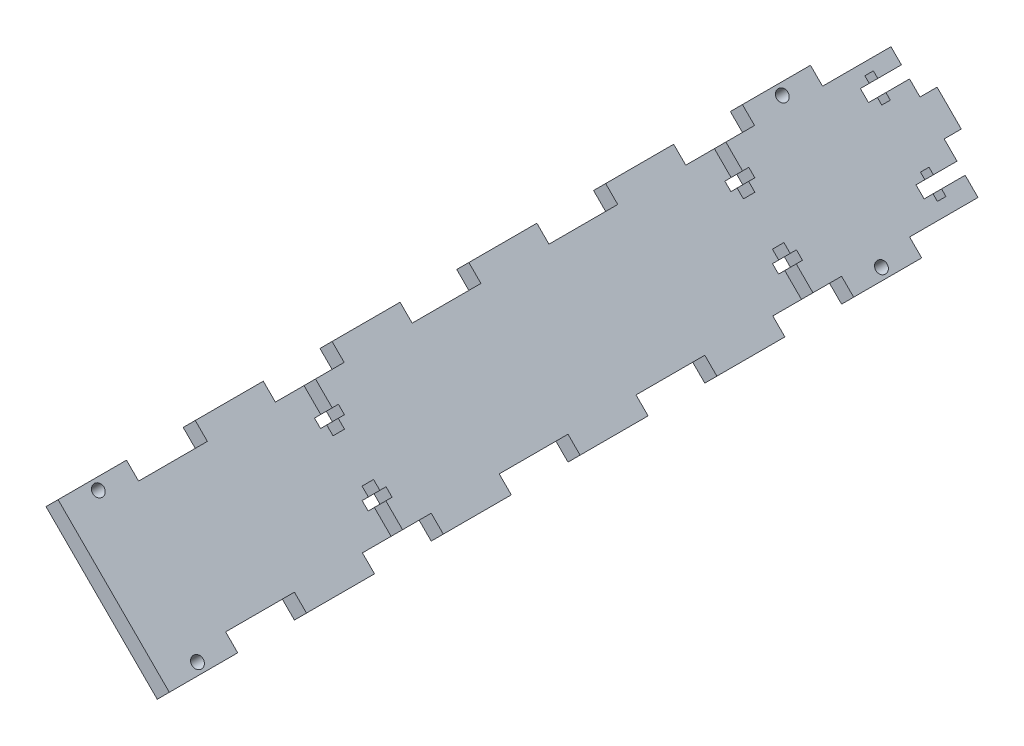
SolidWorks part; units mm, degrees
ref_plane "Front Plane" through (0, 0, 0) normal (0, 0, 1) x (1, 0, 0)
ref_plane "Top Plane" through (0, 0, 0) normal (0, 1, 0) x (1, 0, 0)
ref_plane "Right Plane" through (0, 0, 0) normal (1, 0, 0) x (0, 0, -1)
sketch "Sketch1" plane through (0, 0, 0) normal (0, 0, 1) x (1, 0, 0)
  line L0 (69.148, 48.095) -> (110.4572, 6.7859)
  line L1 (69.148, 48.095) -> (73.6381, 52.5852)
  line L2 (110.4572, 6.7859) -> (114.9473, 11.276)
  line L3 (73.6381, 52.5852) -> (114.9473, 11.276)
  line L4 (74.5361, -29.1352) -> (70.046, -24.645) construction
extrude "Boss-Extrude1" add sketch "Sketch1" along normal up to surface (304.8 mm away)
sketch "Sketch2" plane through (63.1116, 63.1116, 0) normal (0.7071, 0.7071, 0) x (0, 0, -1)
  line L0 (-304.8, -14.8867) -> (0, -14.8867) construction
  line L1 (-279.4, -21.2367) -> (-253.8574, -21.2367)
  line L2 (-279.4, -21.2367) -> (-279.4, -14.8867)
  line L3 (-279.4, -14.8867) -> (-253.8574, -14.8867)
  line L4 (-253.8574, -21.2367) -> (-253.8574, -14.8867)
  line L5 (-304.8, -73.3067) -> (0, -73.3067) construction
  line L6 (-279.4, -66.9567) -> (-253.8574, -66.9567)
  line L7 (-279.4, -66.9567) -> (-279.4, -73.3067)
  line L8 (-279.4, -73.3067) -> (-253.8574, -73.3067)
  line L9 (-253.8574, -66.9567) -> (-253.8574, -73.3067)
extrude "Cut-Extrude1" cut sketch "Sketch2" against normal blind 6.35
pattern_linear "LPattern1" count 6 spacing 50.8 along (0, 0, -1) of "Cut-Extrude1"
sketch "Sketch3" plane through (0, 0, 0) normal (0, 0, -1) x (-1, 0, 0)
  line L0 (-84.4262, 32.8169) -> (-93.4064, 23.8366)
  line L1 (-73.6381, 43.6049) -> (-105.967, 11.276) construction
  line L2 (-93.4064, 23.8366) -> (-97.8965, 28.3267)
  line L3 (-110.4572, 15.7661) -> (-78.1282, 48.095) construction
  line L4 (-97.8965, 28.3267) -> (-88.9163, 37.307)
  line L5 (-88.9163, 37.307) -> (-84.4262, 32.8169)
  dimension "D1" = 21.6066
  dimension "D2" = 12.7
extrude "Boss-Extrude2" add sketch "Sketch3" along normal blind 6.35
sketch "Sketch4" plane through (58.6215, 58.6215, 0) normal (-0.7071, -0.7071, 0) x (-0.7071, 0.7071, 0)
  line L0 (-28.865, -4.261) -> (-28.865, -30.7468) construction
  line L1 (-58.075, -4.261) -> (-58.075, -30.7468) construction
  line L2 (-66.9567, 0) -> (-66.9567, -25.4) construction
  line L3 (-49.1933, 6.35) -> (-49.1933, 0) construction
  line L4 (-36.4933, 6.35) -> (-36.4933, 0) construction
  line L5 (-21.2367, -25.4) -> (-21.2367, 0) construction
  line L6 (-49.1933, 0) -> (-66.9567, 0) construction
  line L7 (-21.2367, 0) -> (-36.4933, 0) construction
  line B0 (-55.9414, 0) -> (-60.2086, 0)
  line B1 (-60.2086, -11.938) -> (-62.52, -11.938)
  line B2 (-62.52, -11.938) -> (-62.52, -8.763)
  line B3 (-62.52, -8.763) -> (-60.2086, -8.763)
  line B4 (-60.2086, -8.763) -> (-60.2086, 0)
  line B5 (-60.2086, -11.938) -> (-60.2086, -15.24)
  line B6 (-60.2086, -15.24) -> (-55.9414, -15.24)
  line B7 (-55.9414, -11.938) -> (-55.9414, -15.24)
  line B8 (-55.9414, -8.763) -> (-55.9414, 0)
  line B9 (-53.63, -8.763) -> (-55.9414, -8.763)
  line B10 (-53.63, -11.938) -> (-53.63, -8.763)
  line B11 (-55.9414, -11.938) -> (-53.63, -11.938)
  line B12 (-26.7314, 0) -> (-30.9986, 0)
  line B13 (-30.9986, -11.938) -> (-33.31, -11.938)
  line B14 (-33.31, -11.938) -> (-33.31, -8.763)
  line B15 (-33.31, -8.763) -> (-30.9986, -8.763)
  line B16 (-30.9986, -8.763) -> (-30.9986, 0)
  line B17 (-30.9986, -11.938) -> (-30.9986, -15.24)
  line B18 (-30.9986, -15.24) -> (-26.7314, -15.24)
  line B19 (-26.7314, -11.938) -> (-26.7314, -15.24)
  line B20 (-26.7314, -8.763) -> (-26.7314, 0)
  line B21 (-24.42, -8.763) -> (-26.7314, -8.763)
  line B22 (-24.42, -11.938) -> (-24.42, -8.763)
  line B23 (-26.7314, -11.938) -> (-24.42, -11.938)
sketch_block_instance "TSlot-1"
sketch_block "TSlot" parameters "D1"=3.302, "D2"=3.175
sketch_block_instance "TSlot-2"
extrude "Cut-Extrude2" cut sketch "Sketch4" against normal through all
sketch "Sketch5" plane through (58.6215, 58.6215, 0) normal (-0.7071, -0.7071, 0) x (-0.7071, 0.7071, 0)
  line L0 (-14.8867, -289.9664) -> (-21.2367, -294.2336) construction
  line L1 (-14.8867, -304.8) -> (-14.8867, -279.4) construction
  line L2 (-21.2367, -289.9664) -> (-14.8867, -289.9664) construction
  line L3 (-21.2367, -289.9664) -> (-14.8867, -294.2336) construction
  line L4 (-21.2367, -294.2336) -> (-14.8867, -294.2336) construction
  line L11 (-21.2367, -40.2336) -> (-14.8867, -35.9664) construction
  line L12 (-14.8867, -50.6574) -> (-14.8867, -25.4) construction
  line L13 (-21.2367, -35.9664) -> (-14.8867, -35.9664) construction
  line L14 (-21.2367, -35.9664) -> (-14.8867, -40.2336) construction
  line L15 (-21.2367, -40.2336) -> (-14.8867, -40.2336) construction
  circle A0 centre (-18.0617, -38.1) radius 2.0955
  circle A2 centre (-18.0617, -292.1) radius 2.0955
  dimension "D1" = 4.191
extrude "Cut-Extrude3" cut sketch "Sketch5" against normal through all
ref_plane "Midplane" through (31.1811, -31.1811, 0) normal (0.7071, -0.7071, 0) x (0, 0, -1)
mirror "Mirror1" about plane through (31.1811, -31.1811, 0) normal (0.7071, -0.7071, 0) of "Cut-Extrude3"
sketch "Sketch6" plane through (58.6215, 58.6215, 0) normal (-0.7071, -0.7071, 0) x (-0.7071, 0.7071, 0)
  line L0 (0, -215.8287) -> (-47.8431, -215.8287) construction
  line L1 (32.2115, -63.4287) -> (-38.3785, -63.4287) construction
  line L2 (-21.2367, -50.6574) -> (-14.8867, -50.6574) construction
  line L3 (-14.8867, -76.2) -> (-21.2367, -76.2) construction
  line L4 (-21.2367, -203.0574) -> (-14.8867, -203.0574) construction
  line L5 (-14.8867, -228.6) -> (-21.2367, -228.6) construction
  line L6 (-21.2367, -76.2) -> (-21.2367, -50.6574) construction
  line L7 (-21.2367, -228.6) -> (-21.2367, -203.0574) construction
  line B0 (-21.2367, -65.5623) -> (-21.2367, -61.2951)
  line B1 (-33.1747, -61.2951) -> (-33.1747, -58.9837)
  line B2 (-33.1747, -58.9837) -> (-29.9997, -58.9837)
  line B3 (-29.9997, -58.9837) -> (-29.9997, -61.2951)
  line B4 (-29.9997, -61.2951) -> (-21.2367, -61.2951)
  line B5 (-33.1747, -61.2951) -> (-36.4767, -61.2951)
  line B6 (-36.4767, -61.2951) -> (-36.4767, -65.5623)
  line B7 (-33.1747, -65.5623) -> (-36.4767, -65.5623)
  line B8 (-29.9997, -65.5623) -> (-21.2367, -65.5623)
  line B9 (-29.9997, -67.8737) -> (-29.9997, -65.5623)
  line B10 (-33.1747, -67.8737) -> (-29.9997, -67.8737)
  line B11 (-33.1747, -65.5623) -> (-33.1747, -67.8737)
  line B12 (-21.2367, -217.9623) -> (-21.2367, -213.6951)
  line B13 (-33.1747, -213.6951) -> (-33.1747, -211.3837)
  line B14 (-33.1747, -211.3837) -> (-29.9997, -211.3837)
  line B15 (-29.9997, -211.3837) -> (-29.9997, -213.6951)
  line B16 (-29.9997, -213.6951) -> (-21.2367, -213.6951)
  line B17 (-33.1747, -213.6951) -> (-36.4767, -213.6951)
  line B18 (-36.4767, -213.6951) -> (-36.4767, -217.9623)
  line B19 (-33.1747, -217.9623) -> (-36.4767, -217.9623)
  line B20 (-29.9997, -217.9623) -> (-21.2367, -217.9623)
  line B21 (-29.9997, -220.2737) -> (-29.9997, -217.9623)
  line B22 (-33.1747, -220.2737) -> (-29.9997, -220.2737)
  line B23 (-33.1747, -217.9623) -> (-33.1747, -220.2737)
sketch_block_instance "TSlot-3"
sketch_block_instance "TSlot-4"
extrude "Cut-Extrude4" cut sketch "Sketch6" against normal through all
mirror "Mirror2" about plane through (31.1811, -31.1811, 0) normal (0.7071, -0.7071, 0) of "Cut-Extrude4"
